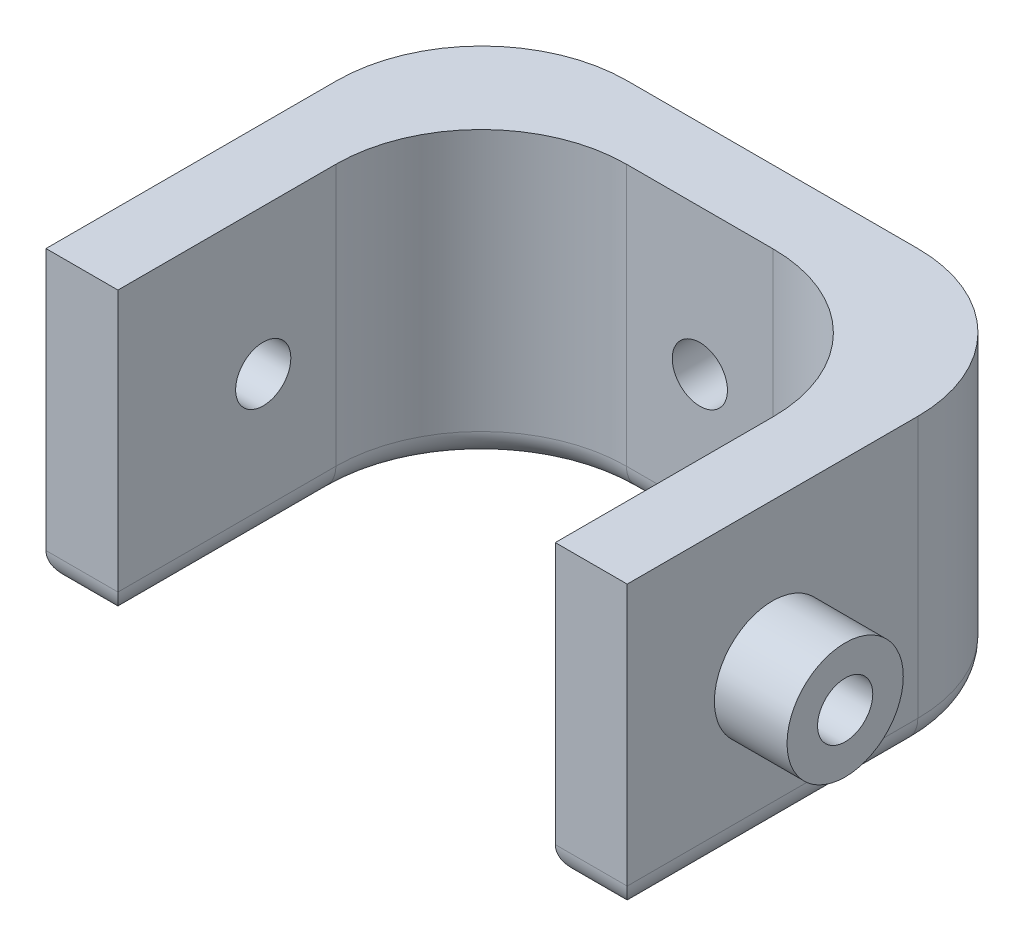
SolidWorks part; units mm, degrees
ref_plane "Front Plane" through (0, 0, 0) normal (0, 0, 1) x (1, 0, 0)
ref_plane "Top Plane" through (0, 0, 0) normal (0, 1, 0) x (1, 0, 0)
ref_plane "Right Plane" through (0, 0, 0) normal (1, 0, 0) x (0, 0, -1)
sketch "Sketch1" plane through (0, 0, 0) normal (0, 1, 0) x (1, 0, 0)
  line L0 (-36.1783, 0) -> (41.9108, 0) construction
  line L1 (-20, 15) -> (20, 15)
  line L2 (-20, 15) -> (-20, -15)
  line L3 (-20, -15) -> (-15.05, -15)
  line L4 (20, 15) -> (20, -15)
  line L5 (15.05, -15) -> (20, -15)
  line L6 (0, 35.9873) -> (0, -18.6969) construction
  line L8 (-15.05, -15) -> (-15.05, 10)
  line L9 (-15.05, 10) -> (15.05, 10)
  line L10 (15.05, -15) -> (15.05, 10)
  dimension "D1" = 40
  dimension "D2" = 30
  dimension "D3" = 30.1
  dimension "D4" = 25
extrude "Boss-Extrude1" add sketch "Sketch1" along normal blind 20
fillet "Fillet1" radius 10 4 edges at (-20, 10, -15) (20, 10, -15) (15.05, 10, -10) (-15.05, 10, -10)
sketch "Sketch2" plane through (20, 0, 0) normal (1, 0, 0) x (0, 0, -1)
  line L0 (-5, 20.0557) -> (-5, -1.5673) construction
  line L2 (-14.4095, 10) -> (10.7684, 10) construction
  line L4 (-15, 20) -> (5, 20) construction
  line L5 (-15, 20) -> (-15, 0) construction
  circle A0 centre (-5, 10) radius 4
  circle A1 centre (-5, 10) radius 1.9
  point P7 (0, 0)
  point P10 (-5, 20)
  point P13 (-15, 10)
  dimension "D1" = 8
  dimension "D2" = 3.8
extrude "Boss-Extrude2" add sketch "Sketch2" along normal blind 5
mirror "Mirror1" about plane through (0, 0, 0) normal (1, 0, 0) of "Boss-Extrude2"
sketch "Sketch3" plane through (20, 0, 0) normal (1, 0, 0) x (0, 0, -1)
  circle A0 centre (-5, 10) radius 1.9
  circle A1 centre (-5, 10) radius 1.9 construction
extrude "Cut-Extrude1" cut sketch "Sketch3" against normal through all
sketch "Sketch5" plane through (0, 0, -15) normal (0, 0, -1) x (-1, 0, 0)
  line L0 (-37.173, 10) -> (31.5318, 10) construction
  line L1 (10, 0) -> (10, 20) construction
  circle A0 centre (0, 10) radius 1.9
  circle A1 centre (0, 10) radius 4
  point P8 (10, 10)
  point P9 (0, 0)
  dimension "D1" = 3.8
  dimension "D2" = 8
extrude "Boss-Extrude3" add sketch "Sketch5" along normal blind 5
sketch "Sketch6" plane through (0, 0, -15) normal (0, 0, -1) x (-1, 0, 0)
  circle A0 centre (0, 10) radius 1.9
  circle A1 centre (0, 10) radius 1.9 construction
extrude "Cut-Extrude2" cut sketch "Sketch6" against normal through all
fillet "Fillet2" radius 2 12 edges at (-17.525, 0, 15) (-15.05, 0, 7.5) (-12.1211, 0, -7.0711) (0, 0, -10) (12.1211, 0, -7.0711) (15.05, 0, 7.5) (17.525, 0, 15) (20, 0, 5) (17.0711, 0, -12.0711) (0, 0, -15) (-17.0711, 0, -12.0711) (-20, 0, 5)
